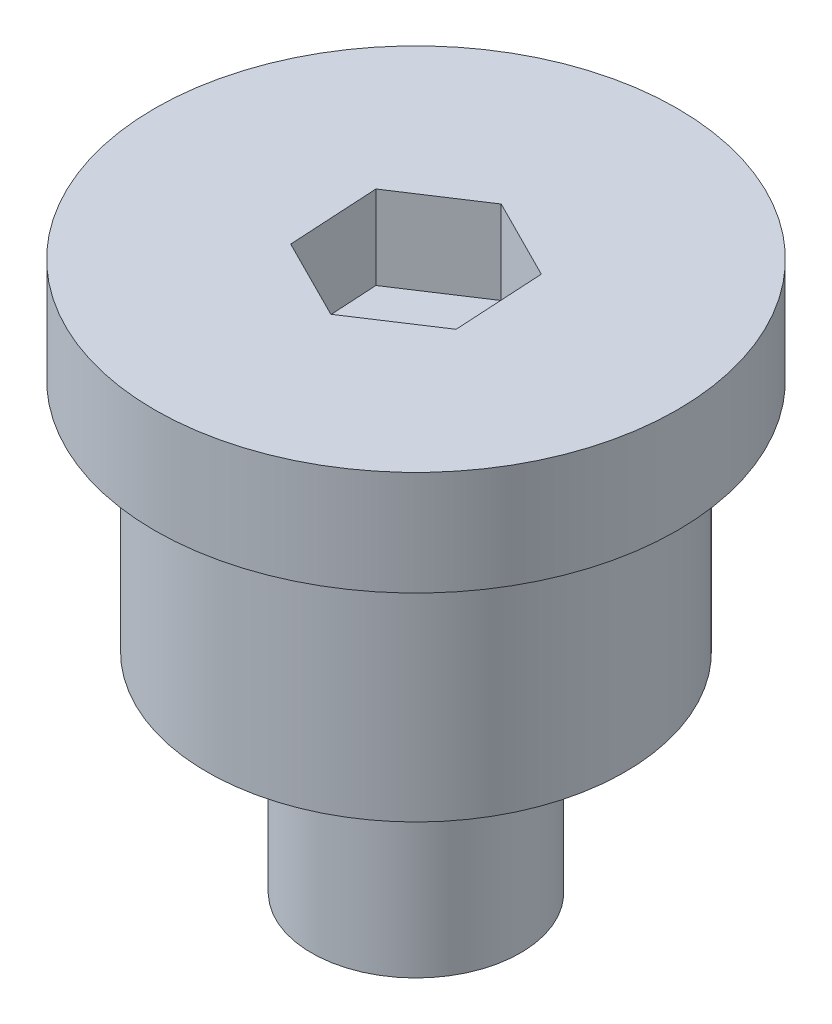
SolidWorks part; units mm, degrees
material "6061-T6 (SS)"
ref_plane "Front Plane" through (0, 0, 0) normal (0, 0, 1) x (1, 0, 0)
ref_plane "Top Plane" through (0, 0, 0) normal (0, 1, 0) x (1, 0, 0)
ref_plane "Right Plane" through (0, 0, 0) normal (1, 0, 0) x (0, 0, -1)
sketch "Sketch1" plane through (0, 0, 0) normal (1, 0, 0) x (0, 0, -1)
  line L0 (0, 0) -> (0, 16.6726)
  line L1 (0, 16.6726) -> (-7.9375, 16.6726)
  line L2 (-7.9375, 16.6726) -> (-7.9375, 13.4976)
  line L3 (-7.9375, 13.4976) -> (-6.35, 13.4976)
  line L4 (-6.35, 13.4976) -> (-6.35, 6.35)
  line L5 (-6.35, 6.35) -> (-3.175, 6.35)
  line L6 (-3.175, 6.35) -> (-3.175, 0)
  line L7 (-3.175, 0) -> (0, 0)
  dimension "D1" = 6.35
  dimension "D2" = 7.1476
  dimension "D3" = 3.175
  dimension "D4" = 7.9375
  dimension "D5" = 3.175
  dimension "D6" = 6.35
revolve "Revolve1" add sketch "Sketch1" angle 360 about L0
sketch "Sketch2" plane through (0, 16.6726, 0) normal (0, 1, 0) x (1, 0, 0)
  line L1 (-2.2994, -1.5078) -> (0.1561, -2.7452)
  line L2 (0.1561, -2.7452) -> (2.4555, -1.2374)
  line L3 (2.4555, -1.2374) -> (2.2994, 1.5078)
  line L4 (2.2994, 1.5078) -> (-0.1561, 2.7452)
  line L5 (-0.1561, 2.7452) -> (-2.4555, 1.2374)
  line L6 (-2.4555, 1.2374) -> (-2.2994, -1.5078)
  circle A1 centre (0, 0) radius 2.3813 construction
  dimension "D1" = 4.7625
extrude "Cut-Extrude1" cut sketch "Sketch2" against normal blind 2.54
